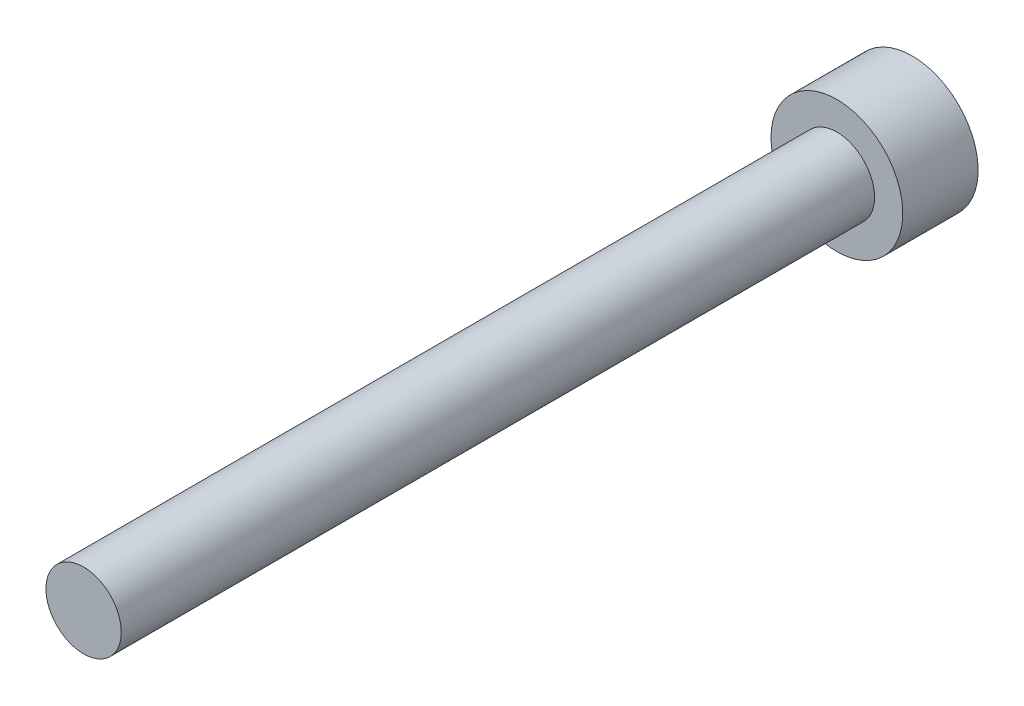
SolidWorks part; units mm, degrees
ref_plane "Front Plane" through (0, 0, 0) normal (0, 0, 1) x (1, 0, 0)
ref_plane "Top Plane" through (0, 0, 0) normal (0, 1, 0) x (1, 0, 0)
ref_plane "Right Plane" through (0, 0, 0) normal (1, 0, 0) x (0, 0, -1)
ref_plane "Plane1" through (0, 0, 0) normal (0, -1, 0) x (1, 0, 0)
sketch "Sketch1" plane through (0, 0, 0) normal (0, -1, 0) x (1, 0, 0)
  line L0 (3.5, 4) -> (0, 4)
  line L1 (0, 4) -> (0, 0)
  line L2 (0, 0) -> (3.5, 0)
  line L3 (3.5, 0) -> (3.5, 4)
  line L4 (0, 4) -> (0, 0) construction
revolve "Revolve1" add sketch "Sketch1" angle 360 about L4
sketch "Sketch2" plane through (0, 0, 4) normal (0, 0, 1) x (1, 0, 0)
  circle A0 centre (0, 0) radius 2
extrude "Boss-Extrude1" add sketch "Sketch2" along normal blind 20
sketch "Sketch3" plane through (0, 0, 24) normal (0, 0, 1) x (1, 0, 0)
  circle A0 centre (0, 0) radius 2
extrude "Boss-Extrude2" add sketch "Sketch3" along normal blind 20
sketch "Sketch4" plane through (0, 0, 0) normal (0, 0, -1) x (-1, 0, 0)
  line L0 (-1.7, 0) -> (-0.85, -1.4722)
  line L1 (-0.85, -1.4722) -> (0.85, -1.4722)
  line L2 (0.85, -1.4722) -> (1.7, 0)
  line L3 (1.7, 0) -> (0.85, 1.4722)
  line L4 (0.85, 1.4722) -> (-0.85, 1.4722)
  line L5 (-0.85, 1.4722) -> (-1.7, 0)
extrude "Cut-Extrude1" cut sketch "Sketch4" against normal blind 2.4
